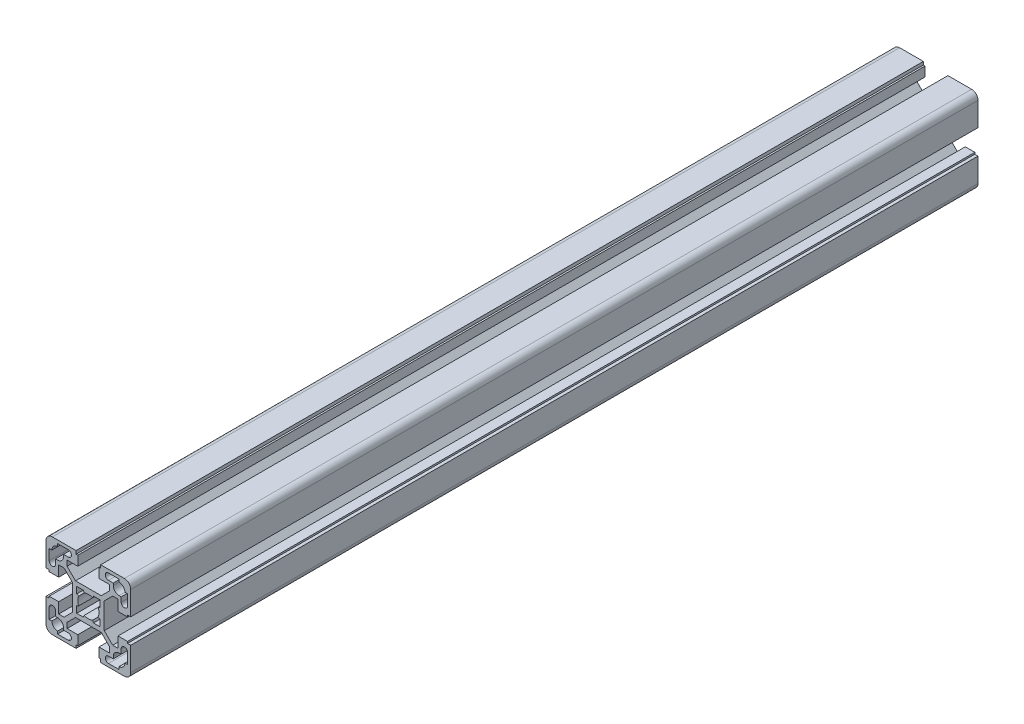
SolidWorks part; units mm, degrees
material "6061 Alloy"
ref_plane "Front Plane" through (0, 0, 0) normal (0, 0, 1) x (1, 0, 0)
ref_plane "Top Plane" through (0, 0, 0) normal (0, 1, 0) x (1, 0, 0)
ref_plane "Right Plane" through (0, 0, 0) normal (1, 0, 0) x (0, 0, -1)
sketch "Sketch1" plane through (0, 0, 0) normal (0, 0, 1) x (1, 0, 0)
  line L0 (5.8, -20) -> (17, -20)
  line L1 (14, -10.05) -> (11.4642, -10.05)
  line L2 (0, -21.1722) -> (0, 18.817) construction
  line L3 (0, 21.1722) -> (0, -18.817) construction
  line L4 (14.5, -18.5) -> (9.5, -18.5)
  line L5 (18.5, 5) -> (14, 5)
  line L6 (6.0858, -7.5) -> (10.05, -11.4642)
  line L7 (20, 5.8) -> (18.5, 5.8)
  line L8 (14, 5) -> (14, 10.05)
  line L9 (18.5, 5.8) -> (18.5, 5)
  line L10 (18.5, 14.5) -> (17.25, 14.5)
  line L11 (14.5, 11.75) -> (15.5, 11.75)
  line L12 (14.5, 17.25) -> (14.5, 18.5)
  line L13 (18.5, 9.5) -> (18.5, 14.5)
  line L14 (15.5, 11.75) -> (15.5, 9.5)
  line L15 (20, 17) -> (20, 5.8)
  line L16 (5.5, 5.5) -> (2.3979, 5.5)
  line L17 (2.3979, 5.5) -> (1.9983, 4.5833)
  line L18 (5.5, 2.3979) -> (5.5, 5.5)
  line L19 (4.5833, 1.9983) -> (5.5, 2.3979)
  line L20 (5, -14) -> (5, -18.5)
  line L21 (11.4642, 10.05) -> (7.5, 6.0858)
  line L22 (-6.0858, 7.5) -> (6.0858, 7.5)
  line L23 (11.75, 15.5) -> (11.75, 14.5)
  line L24 (5, -18.5) -> (5.8, -18.5)
  line L25 (5.8, -18.5) -> (5.8, -20)
  line L26 (10.05, -11.4642) -> (10.05, -14)
  line L27 (10.05, -14) -> (5, -14)
  line L28 (9.5, -15.5) -> (11.75, -15.5)
  line L29 (11.75, -15.5) -> (11.75, -14.5)
  line L30 (9.5, 15.5) -> (11.75, 15.5)
  line L31 (10.05, 14) -> (5, 14)
  line L32 (10.05, 11.4642) -> (10.05, 14)
  line L33 (5.8, 18.5) -> (5.8, 20)
  line L34 (5, 18.5) -> (5.8, 18.5)
  line L35 (7.5, -6.0858) -> (7.5, 6.0858)
  line L36 (5, 14) -> (5, 18.5)
  line L37 (6.0858, 7.5) -> (10.05, 11.4642)
  line L38 (14.5, 18.5) -> (9.5, 18.5)
  line L39 (14, 10.05) -> (11.4642, 10.05)
  line L40 (5.8, 20) -> (17, 20)
  line L41 (-18.5, -5) -> (-14, -5)
  line L42 (-6.0858, -7.5) -> (6.0858, -7.5)
  line L43 (11.4642, -10.05) -> (7.5, -6.0858)
  line L44 (-20, -5.8) -> (-18.5, -5.8)
  line L45 (-14, -5) -> (-14, -10.05)
  line L46 (-18.5, -5.8) -> (-18.5, -5)
  line L47 (-18.5, -14.5) -> (-17.25, -14.5)
  line L48 (4.5833, -1.9983) -> (5.5, -2.3979)
  line L49 (5.5, -2.3979) -> (5.5, -5.5)
  line L50 (2.3979, -5.5) -> (1.9983, -4.5833)
  line L51 (5.5, -5.5) -> (2.3979, -5.5)
  line L52 (-14.5, -11.75) -> (-15.5, -11.75)
  line L53 (-14.5, -17.25) -> (-14.5, -18.5)
  line L54 (-18.5, -9.5) -> (-18.5, -14.5)
  line L55 (-15.5, -11.75) -> (-15.5, -9.5)
  line L56 (-20, -17) -> (-20, -5.8)
  line L57 (-5.5, -5.5) -> (-2.3979, -5.5)
  line L58 (-2.3979, -5.5) -> (-1.9983, -4.5833)
  line L59 (-5.5, -2.3979) -> (-5.5, -5.5)
  line L60 (-4.5833, -1.9983) -> (-5.5, -2.3979)
  line L61 (-11.4642, -10.05) -> (-7.5, -6.0858)
  line L62 (-5.8, 20) -> (-17, 20)
  line L63 (-14, 10.05) -> (-11.4642, 10.05)
  line L64 (-14.5, 18.5) -> (-9.5, 18.5)
  line L65 (-6.0858, 7.5) -> (-10.05, 11.4642)
  line L66 (-5, 14) -> (-5, 18.5)
  line L67 (-7.5, -6.0858) -> (-7.5, 6.0858)
  line L68 (-5, 18.5) -> (-5.8, 18.5)
  line L69 (-5.8, 18.5) -> (-5.8, 20)
  line L70 (-10.05, 11.4642) -> (-10.05, 14)
  line L71 (-10.05, 14) -> (-5, 14)
  line L72 (-9.5, 15.5) -> (-11.75, 15.5)
  line L73 (-11.75, -15.5) -> (-11.75, -14.5)
  line L74 (-9.5, -15.5) -> (-11.75, -15.5)
  line L75 (-10.05, -14) -> (-5, -14)
  line L76 (-10.05, -11.4642) -> (-10.05, -14)
  line L77 (-5.8, -18.5) -> (-5.8, -20)
  line L78 (-5, -18.5) -> (-5.8, -18.5)
  line L79 (-11.75, 15.5) -> (-11.75, 14.5)
  line L80 (-11.4642, 10.05) -> (-7.5, 6.0858)
  line L81 (-5, -14) -> (-5, -18.5)
  line L82 (-4.5833, 1.9983) -> (-5.5, 2.3979)
  line L83 (-5.5, 2.3979) -> (-5.5, 5.5)
  line L84 (-2.3979, 5.5) -> (-1.9983, 4.5833)
  line L85 (-5.5, 5.5) -> (-2.3979, 5.5)
  line L86 (-20, 17) -> (-20, 5.8)
  line L87 (-15.5, 11.75) -> (-15.5, 9.5)
  line L88 (20, -17) -> (20, -5.8)
  line L89 (15.5, -11.75) -> (15.5, -9.5)
  line L90 (18.5, -9.5) -> (18.5, -14.5)
  line L91 (14.5, -17.25) -> (14.5, -18.5)
  line L92 (14.5, -11.75) -> (15.5, -11.75)
  line L93 (18.5, -14.5) -> (17.25, -14.5)
  line L94 (-18.5, 9.5) -> (-18.5, 14.5)
  line L95 (-14.5, 17.25) -> (-14.5, 18.5)
  line L96 (18.5, -5.8) -> (18.5, -5)
  line L97 (14, -5) -> (14, -10.05)
  line L98 (20, -5.8) -> (18.5, -5.8)
  line L99 (18.5, -5) -> (14, -5)
  line L100 (-14.5, 11.75) -> (-15.5, 11.75)
  line L101 (-18.5, 14.5) -> (-17.25, 14.5)
  line L102 (-18.5, 5.8) -> (-18.5, 5)
  line L103 (-14, 5) -> (-14, 10.05)
  line L104 (-20, 5.8) -> (-18.5, 5.8)
  line L105 (-6.0858, -7.5) -> (-10.05, -11.4642)
  line L106 (-18.5, 5) -> (-14, 5)
  line L107 (-14.5, -18.5) -> (-9.5, -18.5)
  line L108 (-20, 0) -> (20.788, 0) construction
  line L109 (-14, -10.05) -> (-11.4642, -10.05)
  line L110 (-5.8, -20) -> (-17, -20)
  arc A0 (14.5, -11.75) -> (11.75, -14.5) centre (14.5, -14.5) ccw
  arc A1 (18.5, 9.5) -> (15.5, 9.5) centre (17, 9.5) cw
  arc A2 (14.5, 17.25) -> (17.25, 14.5) centre (14.5, 14.5) cw
  arc A3 (17, 20) -> (20, 17) centre (17, 17) cw
  arc A4 (-1.9983, 4.5833) -> (1.9983, 4.5833) centre (0, 0) cw
  arc A5 (9.5, 15.5) -> (9.5, 18.5) centre (9.5, 17) cw
  arc A6 (9.5, -15.5) -> (9.5, -18.5) centre (9.5, -17) ccw
  arc A7 (14.5, 11.75) -> (11.75, 14.5) centre (14.5, 14.5) cw
  arc A8 (4.5833, -1.9983) -> (4.5833, 1.9983) centre (0, 0) ccw
  arc A9 (-18.5, -9.5) -> (-15.5, -9.5) centre (-17, -9.5) cw
  arc A10 (-14.5, -17.25) -> (-17.25, -14.5) centre (-14.5, -14.5) cw
  arc A11 (-1.9983, -4.5833) -> (1.9983, -4.5833) centre (0, 0) ccw
  arc A12 (-17, -20) -> (-20, -17) centre (-17, -17) cw
  arc A13 (-4.5833, -1.9983) -> (-4.5833, 1.9983) centre (0, 0) cw
  arc A14 (-14.5, 11.75) -> (-11.75, 14.5) centre (-14.5, 14.5) ccw
  arc A15 (-9.5, -15.5) -> (-9.5, -18.5) centre (-9.5, -17) cw
  arc A16 (-9.5, 15.5) -> (-9.5, 18.5) centre (-9.5, 17) ccw
  arc A17 (-17, 20) -> (-20, 17) centre (-17, 17) ccw
  arc A18 (17, -20) -> (20, -17) centre (17, -17) ccw
  arc A19 (14.5, -17.25) -> (17.25, -14.5) centre (14.5, -14.5) ccw
  arc A20 (18.5, -9.5) -> (15.5, -9.5) centre (17, -9.5) ccw
  arc A21 (-14.5, 17.25) -> (-17.25, 14.5) centre (-14.5, 14.5) ccw
  arc A22 (-18.5, 9.5) -> (-15.5, 9.5) centre (-17, 9.5) ccw
  arc A23 (-14.5, -11.75) -> (-11.75, -14.5) centre (-14.5, -14.5) cw
  point P55 (7.5, 0)
  point P101 (-7.5, 0)
  point P116 (0, -7.5)
  point P149 (0, 7.5)
extrude "Extrude1" add sketch "Sketch1" along normal blind 400
hole_wizard "M12 Tapped Hole1" [suppressed] positions "3DSketch2" profile "Sketch3" tap size "M12" standard "ISO"
sketch3d "3DSketch2"
  line L0 (-20, 17, 0) -> (-20, 5.8, 0) construction
  line L1 (-5.8, 20, 0) -> (-17, 20, 0) construction
  line L2 (-5.8, 20, 200) -> (-17, 20, 200) construction
  line L3 (-20, 17, 200) -> (-20, 5.8, 200) construction
  point P0 (0, 0, 200)
  point P2 (0, 0, 0)
  dimension "D1" = 20
  dimension "D2" = 20
  dimension "D3" = 20
  dimension "D4" = 20
sketch "Sketch3" plane through (0, 0, 200) normal (1, 0, 0) x (0, -1, 0)
  line L0 (0, 0) -> (0, 35.8144)
  line L1 (0, 35.8144) -> (5.1, 32.75)
  line L2 (5.1, 32.75) -> (5.1, 0.925)
  line L3 (5.1, 0.925) -> (6.025, 0)
  line L5 (6.025, 0) -> (0, 0)
  line L6 (-5.1, 0.925) -> (-6.025, 0) construction
  line L10 (0, 35.8144) -> (-5.1, 32.75) construction
  line L11 (0, -6.35) -> (0, 107.95) construction
  dimension "Tap Drill Dia." = 10.2
  dimension "Tap Drill Depth" = 32.75
  dimension "Near C'Sink Dia." = 12.05
  dimension "Near C'Sink Angle" = 90
  dimension "Drill Angle" = 118
cosmetic thread "Hole Thread1" [suppressed] parameters "D1"=24, "D2"=12
cosmetic thread "Filettatura del foro1" [suppressed] parameters "D1"=24, "D2"=12
hole_wizard "Ø9.8 (9.8) Diameter Hole1" [suppressed] positions "3DSketch3" profile "Sketch4" hole size "Ø9.8" standard "ISO"
sketch3d "3DSketch3"
  line L0 (-5.8, 20, 200) -> (-17, 20, 200) construction
  line L1 (20, -17, 200) -> (20, -5.8, 200) construction
  line L2 (17, 20, 0) -> (5.8, 20, 0) construction
  line L3 (20, -17, 0) -> (20, -5.8, 0) construction
  point P0 (0, 20, 184)
  point P2 (20, 0, 184)
  point P4 (0, 20, 16)
  point P6 (20, 0, 16)
  dimension "D1" = 16
  dimension "D2" = 20
  dimension "D3" = 20
  dimension "D4" = 16
  dimension "D5" = 16
  dimension "D6" = 16
sketch "Sketch4" plane through (0, 20, 184) normal (1, 0, 0) x (0, 0, 1)
  line L0 (0, 0) -> (0, 40)
  line L1 (0, 40) -> (4.9, 40)
  line L2 (4.9, 40) -> (4.9, 0)
  line L5 (4.9, 0) -> (0, 0)
  line L11 (0, -6.35) -> (0, 107.95) construction
  dimension "Thru Hole Dia." = 9.8
  dimension "Thru Hole Depth" = 40
hole_wizard "Ø17.0 (17) Diameter Hole1" [suppressed] positions "3DSketch4" profile "Sketch5" hole size "Ø17.0" standard "ISO"
sketch3d "3DSketch4"
  line L0 (-5.8, 20, 200) -> (-17, 20, 200) construction
  line L1 (-5.8, 20, 0) -> (-17, 20, 0) construction
  point P0 (0, 20, 177.5)
  point P2 (0, 20, 22.5)
  dimension "D1" = 20
  dimension "D2" = 22.5
  dimension "D3" = 22.5
sketch "Sketch5" plane through (0, 20, 177.5) normal (1, 0, 0) x (0, 0, 1)
  line L0 (0, 0) -> (0, 40)
  line L1 (0, 40) -> (8.5, 40)
  line L2 (8.5, 40) -> (8.5, 0)
  line L5 (8.5, 0) -> (0, 0)
  line L11 (0, -6.35) -> (0, 107.95) construction
  dimension "Thru Hole Dia." = 17
  dimension "Thru Hole Depth" = 40
